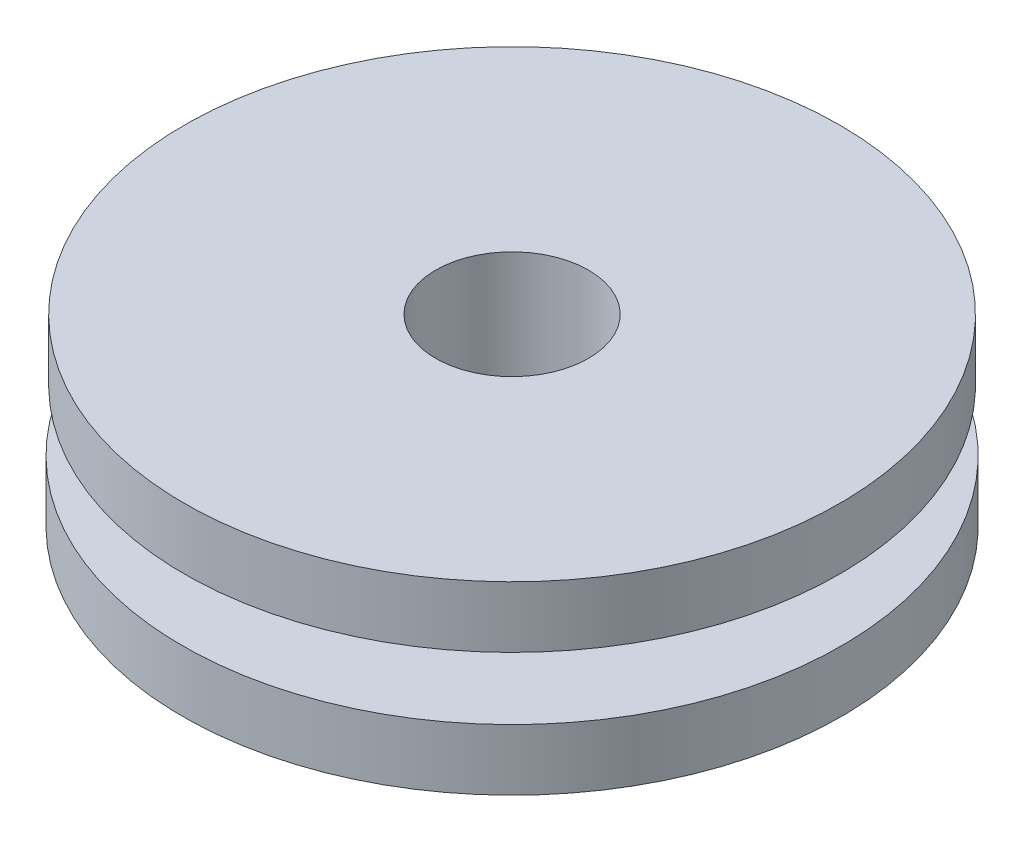
SolidWorks part; units mm, degrees
ref_plane "Front Plane" through (0, 0, 0) normal (1, 0, 0) x (0, 1, 0)
ref_plane "Top Plane" through (0, 0, 0) normal (0, 0, 1) x (0, 1, 0)
ref_plane "Right Plane" through (0, 0, 0) normal (0, 1, 0) x (-1, 0, 0)
sketch "Sketch1" plane through (0, 0, 0) normal (1, 0, 0) x (0, 1, 0)
  line L1 (-14.9999, 0.0274) -> (-14.9999, 15.4156)
  line L2 (-14.9999, 15.4156) -> (-5, 15.4156)
  line L3 (-5, 15.4156) -> (-5, 0.1097)
  line L5 (-14.9999, -25.9561) -> (15, -25.9561)
  line L9 (5, 0.1097) -> (5, 15.1097)
  line L10 (5, 15.1097) -> (15, 15.1097)
  line L13 (15, 15.1097) -> (15, 0.1097)
  line L14 (-15, -38.4561) -> (15, -38.4561) construction
  line L16 (-14.9999, -25.9561) -> (-14.9999, 0.0274)
  line L17 (15, 0.1097) -> (15, -25.9561)
  line L20 (-5, 0.1097) -> (5, 0.1097)
  point P5 (0, 0)
  dimension "D1" = 30
  dimension "D4" = 10
  dimension "D5" = 15
  dimension "D6" = 12.5
revolve "Revolve1" add sketch "Sketch1" angle 360 about L14
sketch "Sketch2" plane through (0, 15, 0) normal (0, 1, 0) x (-1, 0, 0)
  circle A0 centre (0, -38.4561) radius 28.5
  dimension "D1" = 57
